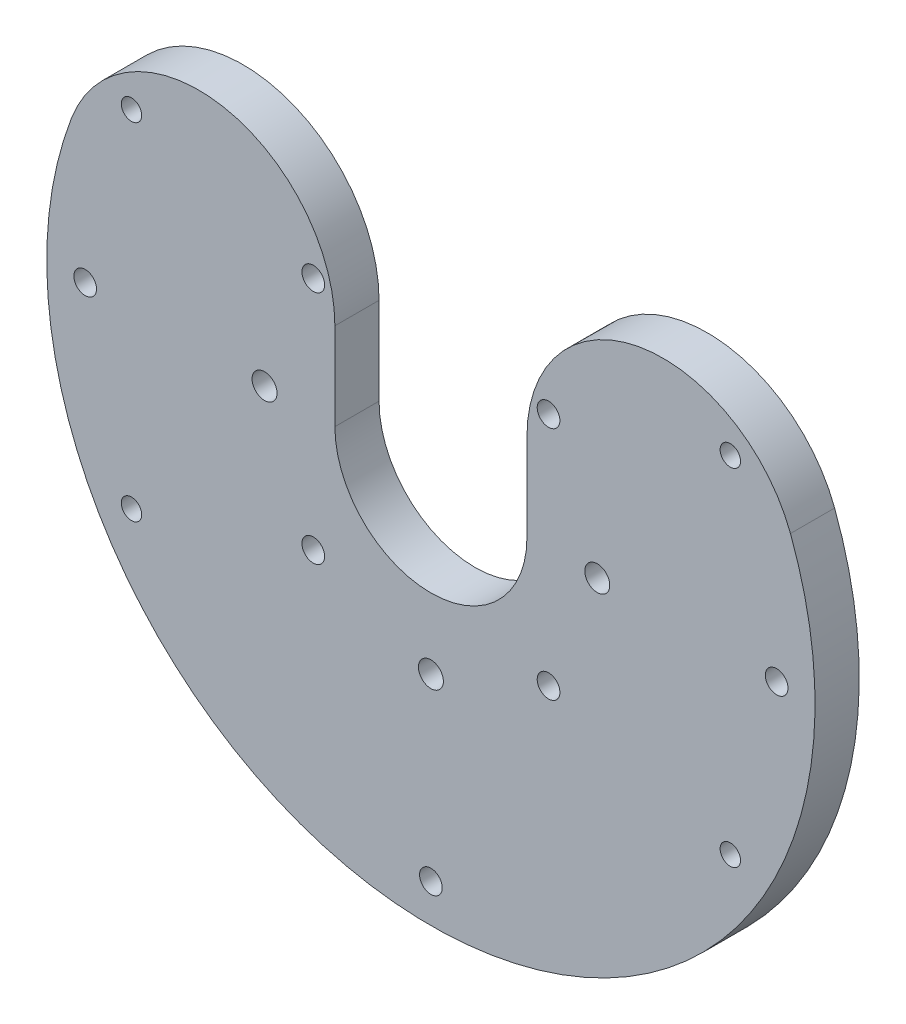
SolidWorks part; units mm, degrees
material "Beech"
ref_plane "Front Plane" through (0, 0, 0) normal (0, 0, 1) x (1, 0, 0)
ref_plane "Top Plane" through (0, 0, 0) normal (0, 1, 0) x (1, 0, 0)
ref_plane "Right Plane" through (0, 0, 0) normal (1, 0, 0) x (0, 0, -1)
sketch "Sketch1" plane through (0, 0, 0) normal (0, 0, 1) x (1, 0, 0)
  line L0 (0, 76.2) -> (0, -50.8) construction
  line L1 (-50.8, 0) -> (-12.7, 0) construction
  line L2 (12.7, 0) -> (22, 0) construction
  line L3 (0, 0) -> (-45.72, 0) construction
  line L4 (-12.7, 0) -> (-12.7, 49.1869)
  line L5 (12.7, 0) -> (12.7, 49.1869)
  line L6 (12.7, 0) -> (50.8, 0) construction
  arc A0 (-12.7, 49.1869) -> (12.7, 49.1869) centre (0, 0) ccw
  arc A1 (-12.7, 0) -> (12.7, 0) centre (0, 0) ccw
  circle A2 centre (22, 0) radius 1.65
  circle A3 centre (0, -22) radius 1.65
  circle A4 centre (-22, 0) radius 1.65
  circle A5 centre (0, 22) radius 1.65 [skipped]
  circle A6 centre (-45.72, 0) radius 1.5
  circle A7 centre (0, 45.72) radius 1.5 [skipped]
  circle A8 centre (45.72, 0) radius 1.5
  circle A9 centre (0, -45.72) radius 1.5
  circle A10 centre (0, 45.72) radius 1.35 construction
  circle A11 centre (39.5947, 22.86) radius 1.35
  circle A12 centre (39.5947, -22.86) radius 1.35
  circle A13 centre (0, -45.72) radius 1.35 construction
  circle A14 centre (-39.5947, -22.86) radius 1.35
  circle A15 centre (-39.5947, 22.86) radius 1.35
  point P20 (0, 0)
  point P29 (0, 0)
  point P39 (0, 0)
  point P41 (0, 0)
  dimension "D1" = 101.6
  dimension "D2" = 25.4
  dimension "D4" = 4
  dimension "D5" = 3.3
  dimension "D7" = 4
  dimension "D8" = 3
  dimension "D9" = 45.72
  dimension "D10" = 2.7
  dimension "D3" = 22
  dimension "D6" = 45.72
  dimension "D11" = 6
extrude "Boss-Extrude1" add sketch "Sketch1" along normal blind 5.842 contours A1 L4 A0 L5 A14 A13 A12 A11 A9 A8 A6 A4 A3 A2
fillet "Fillet1" radius 18 2 edges at (12.7, 49.1869, 2.921) (-12.7, 49.1869, 2.921)
sketch "Sketch2" plane through (0, 0, 5.842) normal (0, 0, 1) x (1, 0, 0)
  line L1 (-15.5563, -15.5563) -> (0, 0) construction
  line L2 (0, 0) -> (0, -22) construction
  circle A0 centre (-15.5563, -15.5563) radius 1.5
  circle A1 centre (-15.5563, 15.5563) radius 1.5
  circle A2 centre (15.5563, 15.5563) radius 1.5
  circle A3 centre (15.5563, -15.5563) radius 1.5
  point P15 (0, 0)
  dimension "D2" = 3
  dimension "D1" = 45
  dimension "D3" = 4
extrude "Cut-Extrude1" cut sketch "Sketch2" against normal through all
